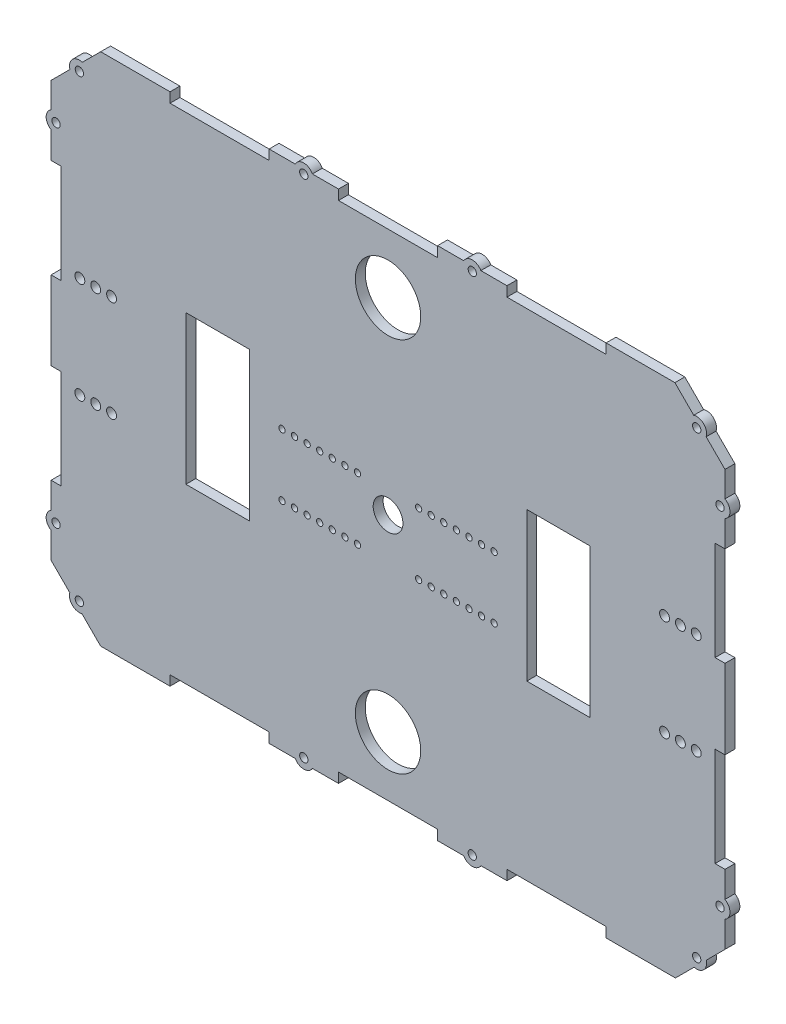
SolidWorks part; units mm, degrees
ref_plane "Plan de face" through (0, 0, 0) normal (0, 0, 1) x (1, 0, 0)
ref_plane "Plan de dessus" through (0, 0, 0) normal (0, 1, 0) x (1, 0, 0)
ref_plane "Plan de droite" through (0, 0, 0) normal (1, 0, 0) x (0, 0, -1)
sketch "Esquisse1" plane through (0, 0, 0) normal (0, 0, 1) x (1, 0, 0)
  line L0 (0, 0) -> (35, 0)
  line L1 (35, 0) -> (35, -5)
  line L2 (35, -5) -> (85, -5)
  line L3 (85, -5) -> (85, 0)
  line L4 (85, 0) -> (98.1699, 0)
  line L5 (120, 0) -> (120, -5)
  line L6 (120, -5) -> (170, -5)
  line L8 (-25, -149.7284) -> (-25, -110)
  line L9 (-25, -25) -> (-25, -37.8983)
  line L10 (-25, -60) -> (-20, -60)
  line L11 (-20, -60) -> (-20, -110)
  line L12 (-20, -110) -> (-25, -110)
  line L14 (-25, -25) -> (-15.5006, -15.5006)
  line L15 (183.1699, -259.7284) -> (170, -259.7284)
  line L16 (-25, -234.7284) -> (-15.5619, -244.1666)
  line L17 (-20, -199.7284) -> (-20, -149.7284)
  line L18 (-25, -199.7284) -> (-20, -199.7284)
  line L19 (-25, -234.7284) -> (-25, -221.5585)
  line L20 (120, -254.7284) -> (170, -254.7284)
  line L21 (120, -259.7284) -> (120, -254.7284)
  line L25 (35, -259.7284) -> (35, -254.7284)
  line L26 (0, -259.7284) -> (35, -259.7284)
  line L27 (-20, -149.7284) -> (-25, -149.7284)
  line L32 (310, -149.7284) -> (315, -149.7284)
  line L33 (290, -259.7284) -> (255, -259.7284)
  line L34 (255, -259.7284) -> (255, -254.7284)
  line L35 (255, -254.7284) -> (205, -254.7284)
  line L36 (205, -254.7284) -> (205, -259.7284)
  line L37 (205, -259.7284) -> (191.8301, -259.7284)
  line L38 (170, -259.7284) -> (170, -254.7284)
  line L39 (315, -234.7284) -> (315, -221.5585)
  line L40 (315, -199.7284) -> (310, -199.7284)
  line L41 (310, -199.7284) -> (310, -149.7284)
  line L42 (315, -234.7284) -> (305.5619, -244.1666)
  line L43 (315, -25) -> (305.5006, -15.5006)
  line L44 (310, -109.7284) -> (315, -109.7284)
  line L45 (310, -59.7284) -> (310, -109.7284)
  line L46 (315, -59.7284) -> (310, -59.7284)
  line L47 (315, -25) -> (315, -37.8983)
  line L48 (170, 0.2716) -> (170, -5)
  line L49 (205, 0.2716) -> (191.8301, 0.2716)
  line L50 (205, -4.7284) -> (205, 0.2716)
  line L51 (255, -4.7284) -> (205, -4.7284)
  line L52 (255, 0.2716) -> (255, -4.7284)
  line L53 (289.7284, 0.2716) -> (255, 0.2716)
  line L54 (106.8301, -259.7284) -> (120, -259.7284)
  line L55 (145, -35) -> (145, -234.7284) construction
  line L56 (-25, -129.8642) -> (20.4156, -129.8642) construction
  line L57 (183.1699, 0.2716) -> (170, 0.2716)
  line L58 (106.8301, 0) -> (120, 0)
  line L59 (-9.2279, -9.2279) -> (0, 0)
  line L60 (215, -167.5) -> (247, -167.5)
  line L61 (-9.4381, -250.2903) -> (0, -259.7284)
  line L62 (299.4381, -250.2903) -> (290, -259.7284)
  line L63 (299.2279, -9.2279) -> (289.7284, 0.2716)
  line L64 (315, -149.7284) -> (315, -109.7284)
  line L65 (247, -92.5) -> (215, -92.5)
  line L66 (43, -92.5) -> (75, -92.5)
  line L67 (75, -92.5) -> (75, -167.5)
  line L68 (75, -167.5) -> (43, -167.5)
  line L69 (43, -167.5) -> (43, -92.5)
  line L70 (215, -92.5) -> (215, -167.5)
  line L71 (247, -167.5) -> (247, -92.5)
  line L72 (85, -259.7284) -> (98.1699, -259.7284)
  line L73 (-25, -217.2284) -> (20.4156, -217.2284) construction
  line L74 (-20, -173.4784) -> (16.3739, -173.4784) construction
  line L75 (315, -46.5585) -> (315, -59.7284)
  line L76 (315, -212.8983) -> (315, -199.7284)
  line L77 (-25, -212.8983) -> (-25, -199.7284)
  line L78 (-25, -46.5585) -> (-25, -60)
  line L81 (85, -254.7284) -> (35, -254.7284)
  line L85 (120, -5) -> (120, -259.7284) construction
  line L88 (85, -254.7284) -> (85, -259.7284)
  circle A0 centre (102.5, -257.2284) radius 2.1
  arc A1 (98.1699, -259.7284) -> (106.8301, -259.7284) centre (102.5, -257.2284) ccw
  arc A2 (191.8301, -259.7284) -> (183.1699, -259.7284) centre (187.5, -257.2284) cw
  circle A3 centre (187.5, -257.2284) radius 2.1
  circle A4 centre (102.5, -2.2284) radius 2.1
  arc A5 (98.1699, 0) -> (106.8301, 0) centre (102.5, -2.2284) cw
  arc A6 (191.8301, 0.2716) -> (183.1699, 0.2716) centre (187.5, -2.2284) ccw
  circle A7 centre (187.5, -2.2284) radius 2.1
  circle A12 centre (-10.7322, -13.9962) radius 2.1
  arc A13 (-9.2279, -9.2279) -> (-15.5006, -15.5006) centre (-10.7322, -13.9962) ccw
  arc A14 (299.2279, -9.2279) -> (305.5006, -15.5006) centre (300.7322, -13.9962) cw
  circle A15 centre (300.7322, -13.9962) radius 2.1
  arc A16 (299.4381, -250.2903) -> (305.5619, -244.1666) centre (300.7322, -245.4607) ccw
  circle A17 centre (300.7322, -245.4607) radius 2.1
  arc A18 (-9.4381, -250.2903) -> (-15.5619, -244.1666) centre (-10.7322, -245.4607) cw
  circle A19 centre (-10.7322, -245.4607) radius 2.1
  arc A22 (-25, -212.8983) -> (-25, -221.5585) centre (-22.5, -217.2284) ccw
  circle A23 centre (-22.5, -217.2284) radius 2.1
  arc A24 (-25, -46.5585) -> (-25, -37.8983) centre (-22.5, -42.2284) cw
  circle A25 centre (-22.5, -42.2284) radius 2.1
  arc A26 (315, -46.5585) -> (315, -37.8983) centre (312.5, -42.2284) ccw
  circle A27 centre (312.5, -42.2284) radius 2.1
  arc A28 (315, -212.8983) -> (315, -221.5585) centre (312.5, -217.2284) cw
  circle A29 centre (312.5, -217.2284) radius 2.1
  circle A32 centre (300.5, -155.2284) radius 2.5
  circle A33 centre (300.5, -104.2284) radius 2.5
  circle A34 centre (145, -35) radius 16.5
  circle A36 centre (145, -129.8642) radius 7.5
  circle A37 centre (292.5, -104.2284) radius 2.5
  circle A38 centre (292.5, -155.2284) radius 2.5
  circle A39 centre (284.5, -104.2284) radius 2.5
  circle A40 centre (284.5, -155.2284) radius 2.5
  circle A47 centre (-10.5, -104.2284) radius 2.5
  circle A48 centre (-2.5, -104.2284) radius 2.5
  circle A49 centre (5.5, -104.2284) radius 2.5
  circle A53 centre (-10.5, -155.2284) radius 2.5
  circle A54 centre (-2.5, -155.2284) radius 2.5
  circle A55 centre (5.5, -155.2284) radius 2.5
  circle A59 centre (260.5, -155.2284) radius 2.5 [skipped]
  circle A60 centre (268.5, -155.2284) radius 2.5 [skipped]
  circle A61 centre (276.5, -155.2284) radius 2.5 [skipped]
  circle A62 centre (260.5, -104.2284) radius 2.5 [skipped]
  circle A63 centre (268.5, -104.2284) radius 2.5 [skipped]
  circle A64 centre (276.5, -104.2284) radius 2.5 [skipped]
  circle A66 centre (145, -224.7284) radius 16.5
  circle A67 centre (91.4717, -119.1854) radius 1.5875
  circle A68 centre (104.1717, -119.1854) radius 1.5875
  circle A69 centre (97.8217, -119.1854) radius 1.5875
  circle A70 centre (110.5217, -119.1854) radius 1.5875
  circle A71 centre (116.8717, -119.1854) radius 1.5875
  circle A72 centre (129.5717, -119.1854) radius 1.5875
  circle A73 centre (123.2217, -119.1854) radius 1.5875
  circle A74 centre (129.5717, -150.4274) radius 1.5875
  circle A75 centre (123.2217, -150.4274) radius 1.5875
  circle A76 centre (116.8717, -150.4274) radius 1.5875
  circle A77 centre (110.5217, -150.4274) radius 1.5875
  circle A78 centre (104.1717, -150.4274) radius 1.5875
  circle A79 centre (97.8217, -150.4274) radius 1.5875
  circle A80 centre (91.4717, -150.4274) radius 1.5875
  circle A81 centre (198.5283, -119.1854) radius 1.5875
  circle A82 centre (192.1783, -119.1854) radius 1.5875
  circle A83 centre (185.8283, -119.1854) radius 1.5875
  circle A84 centre (179.4783, -119.1854) radius 1.5875
  circle A85 centre (173.1283, -119.1854) radius 1.5875
  circle A86 centre (166.7783, -119.1854) radius 1.5875
  circle A87 centre (160.4283, -119.1854) radius 1.5875
  circle A88 centre (160.4283, -150.4274) radius 1.5875
  circle A89 centre (166.7783, -150.4274) radius 1.5875
  circle A90 centre (173.1283, -150.4274) radius 1.5875
  circle A91 centre (179.4783, -150.4274) radius 1.5875
  circle A92 centre (185.8283, -150.4274) radius 1.5875
  circle A93 centre (192.1783, -150.4274) radius 1.5875
  circle A94 centre (198.5283, -150.4274) radius 1.5875
  dimension "D8" = 4.2
  dimension "D14" = 10
  dimension "D15" = 4.2
  dimension "D17" = 63
  dimension "D19" = 10
  dimension "D27" = 33
  dimension "D28" = 30
  dimension "D29" = 15
  dimension "D1" = 35
  dimension "D2" = 50
  dimension "D3" = 5
  dimension "D4" = 35
  dimension "D6" = 5
  dimension "D7" = 35.3553
  dimension "D9" = 35
  dimension "D10" = 5
  dimension "D11" = 50
  dimension "D12" = 5
  dimension "D13" = 43.75
  dimension "D16" = 2.5
  dimension "D20" = 75
  dimension "D21" = 32
  dimension "D26" = 17.5
  dimension "D30" = 6
extrude "Boss.-Extru.1" add sketch "Esquisse1" along normal blind 5
